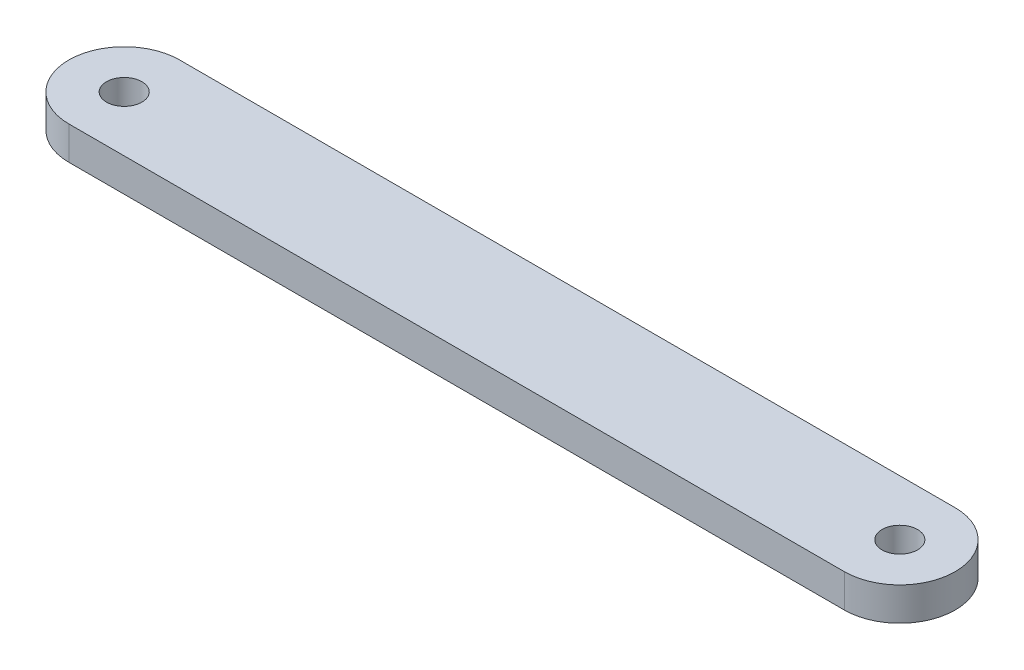
SolidWorks part; units mm, degrees
ref_plane "正面" through (0, 0, 0) normal (0, 0, 1) x (1, 0, 0)
ref_plane "平面" through (0, 0, 0) normal (0, 1, 0) x (1, 0, 0)
ref_plane "右側面" through (0, 0, 0) normal (1, 0, 0) x (0, 0, -1)
sketch "ｽｹｯﾁ1" plane through (0, 0, 0) normal (0, 1, 0) x (1, 0, 0)
  line L0 (0, 0) -> (110, 0) construction
  line L1 (0, -5) -> (70, -5)
  line L3 (0, 5) -> (70, 5)
  circle A0 centre (0, 0) radius 1.6
  circle A1 centre (70, 0) radius 1.6
  arc A2 (0, 5) -> (0, -5) centre (0, 0) ccw
  arc A3 (70, -5) -> (70, 5) centre (70, 0) ccw
  point P1 (0, 0)
  dimension "D5" = 3.2
  dimension "D1" = 5
  dimension "D2" = 10
  dimension "D4" = 70
extrude "ﾎﾞｽ - 押し出し1" add sketch "ｽｹｯﾁ1" along normal blind 3
